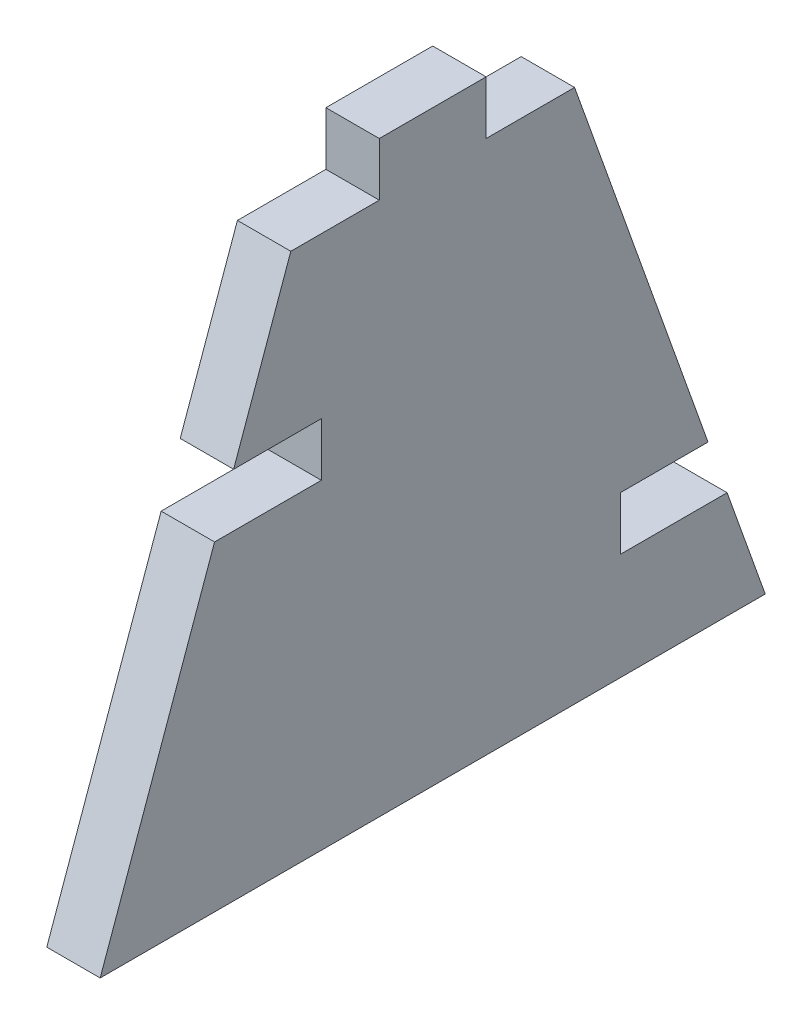
SolidWorks part; units mm, degrees
ref_plane "Front Plane" through (0, 0, 0) normal (0, 0, 1) x (1, 0, 0)
ref_plane "Top Plane" through (0, 0, 0) normal (0, 1, 0) x (1, 0, 0)
ref_plane "Right Plane" through (0, 0, 0) normal (1, 0, 0) x (0, 0, -1)
sketch "Sketch2" plane through (0, 0, 0) normal (1, 0, 0) x (0, 0, -1)
  line L0 (587.8952, 0) -> (-2575.209, 0)
  line L1 (-2575.209, 0) -> (-2031.1752, 1524)
  line L2 (-1668.4861, 2540) -> (-1247.6569, 2540)
  line L3 (-1247.6569, 2540) -> (-1247.6569, 2794)
  line L4 (-1247.6569, 2794) -> (-739.6569, 2794)
  line L5 (-993.6569, 2794) -> (-993.6569, -103.3582) construction
  line L6 (-739.6569, 2540) -> (-739.6569, 2794)
  line L7 (-318.8276, 2540) -> (-739.6569, 2540)
  line L8 (587.8952, 0) -> (406.5506, 508)
  line L10 (-2031.1752, 1524) -> (-1523.1752, 1524)
  line L11 (-1523.1752, 1524) -> (-1523.1752, 1778)
  line L12 (-1523.1752, 1778) -> (-1940.503, 1778)
  line L13 (315.8784, 762) -> (-101.4494, 762)
  line L14 (-101.4494, 762) -> (-101.4494, 508)
  line L15 (-101.4494, 508) -> (406.5506, 508)
  line L16 (-1940.503, 1778) -> (-1668.4861, 2540)
  line L17 (315.8784, 762) -> (-318.8276, 2540)
  dimension "D1" = 3163.1042
  dimension "D2" = 1524
  dimension "D3" = 254
  dimension "D4" = 417.3277
  dimension "D5" = 508
  dimension "D6" = 508
  dimension "D7" = 508
  dimension "D8" = 254
  dimension "D9" = 1778
  dimension "D10" = 2540
extrude "Boss-Extrude1" add sketch "Sketch2" along normal blind 254
